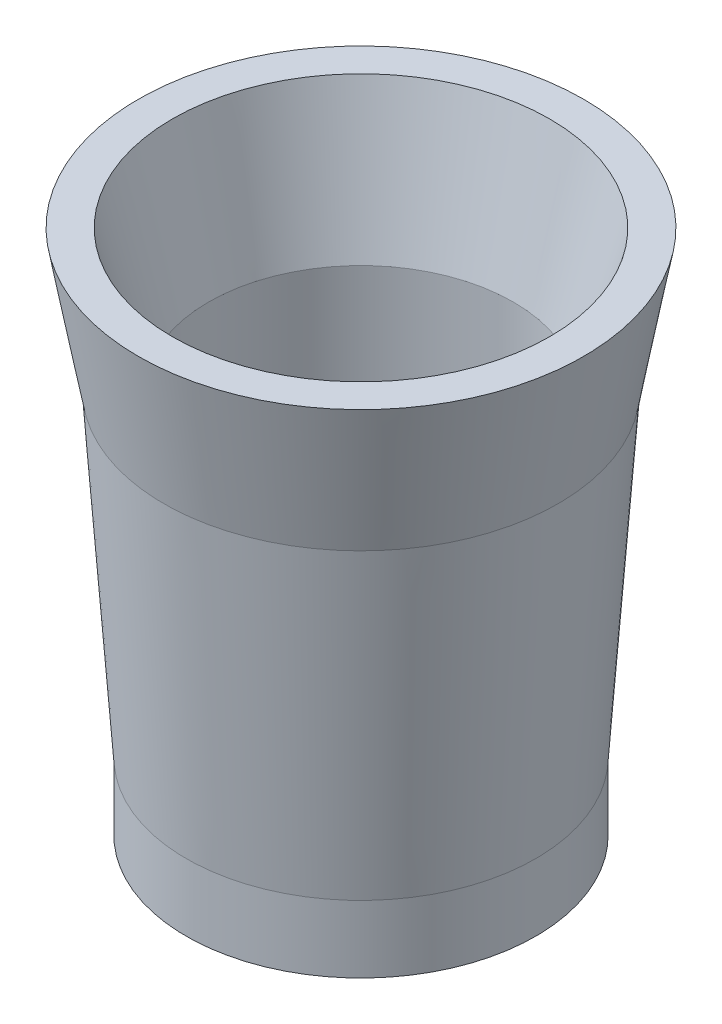
SolidWorks part; units mm, degrees
ref_plane "Front Plane" through (0, 0, 0) normal (0, 0, 1) x (1, 0, 0)
ref_plane "Top Plane" through (0, 0, 0) normal (0, 1, 0) x (1, 0, 0)
ref_plane "Right Plane" through (0, 0, 0) normal (1, 0, 0) x (0, 0, -1)
sketch "Sketch1" plane through (0, 0, 0) normal (0, 0, 1) x (1, 0, 0)
  line L0 (-19.939, 0) -> (19.939, 0) construction
  line L1 (19.939, 0) -> (61.1378, 58.838)
  line L2 (-19.939, 0) -> (-61.1378, 58.838)
  line L3 (-19.939, -109.3403) -> (-19.939, 58.838) construction
  line L4 (19.939, 58.838) -> (19.939, -109.3403) construction
  line L5 (19.939, 0) -> (43.18, -109.3403)
  line L6 (-19.939, 0) -> (-43.18, -109.3403)
  line L7 (0, 0) -> (0, -109.3403) construction
  line L8 (-43.18, -109.3403) -> (43.18, -109.3403) construction
  line L9 (-61.1378, 58.838) -> (61.1378, 58.838) construction
  line L10 (0, 0) -> (0, 58.838) construction
  line L11 (-69.85, 58.838) -> (69.85, 58.838) construction
  line L12 (-76.2, 58.838) -> (76.2, 58.838) construction
  line L13 (-61.1378, 58.838) -> (-69.85, 58.838)
  line L14 (-69.85, 58.838) -> (-69.85, 0)
  line L15 (-69.85, 0) -> (-76.2, 0)
  line L16 (-76.2, 0) -> (-76.2, -109.3403)
  line L17 (-76.2, -109.3403) -> (-43.18, -109.3403)
  line L18 (61.1378, 58.838) -> (69.85, 58.838)
  line L19 (69.85, 58.838) -> (69.85, 0)
  line L20 (69.85, 0) -> (76.2, 0)
  line L21 (76.2, 0) -> (76.2, -109.3403)
  line L22 (76.2, -109.3403) -> (43.18, -109.3403)
  line L23 (69.85, 39.788) -> (47.7988, 39.788)
  line L24 (-69.85, 39.788) -> (-47.7988, 39.788)
  line L25 (-76.2, 0) -> (76.2, 0) construction
  line L26 (-53.4699, 39.788) -> (-43.18, 0)
  line L27 (-43.18, 0) -> (-43.18, -76.2)
  line L28 (-43.18, -109.3403) -> (-43.18, -46.4417) construction
  line L29 (-43.18, -76.2) -> (-36.1358, -76.2)
  line L30 (-63.6778, 58.838) -> (63.6778, 58.838) construction
  line L31 (-69.85, 39.788) -> (-53.4699, 39.788) construction
  line L32 (-55.88, 0) -> (-49.53, -90.2903)
  line L33 (-63.1204, 39.788) -> (-63.1204, 35.0869) construction
  line L34 (-55.88, 0) -> (-63.1204, 39.788)
  line L35 (-43.18, -90.2903) -> (-62.0062, -90.2903) construction
  line L36 (-49.53, -90.2903) -> (-49.53, -109.3403)
  line L37 (43.18, -76.2) -> (36.1358, -76.2)
  line L38 (49.53, -90.2903) -> (49.53, -109.3403)
  line L39 (43.18, 0) -> (43.18, -76.2)
  line L40 (55.88, 0) -> (49.53, -90.2903)
  line L41 (55.88, 0) -> (63.1204, 39.788)
  line L42 (53.4699, 39.788) -> (43.18, 0)
  point P4 (0, 0)
  point P9 (-19.939, -25.2512)
  point P12 (19.939, 0)
  point P16 (0, 0)
  point P20 (0, -109.3403)
  point P22 (0, 58.838)
  point P25 (0, 58.838)
  point P37 (0, 0)
  point P39 (0, 0)
  point P46 (0, 58.838)
  dimension "D1" = 39.878
  dimension "D2" = 35
  dimension "D3" = 35
  dimension "D4" = 122.2756
  dimension "D5" = 12
  dimension "D6" = 86.36
  dimension "D7" = 139.7
  dimension "D8" = 152.4
  dimension "D9" = 19.05
  dimension "D10" = 19.05
  dimension "D11" = 152.4
  dimension "D12" = 20.5
  dimension "D13" = 12.7
  dimension "D14" = 6.35
  dimension "D15" = 127.3556
  dimension "D16" = 76.2
  dimension "D17" = 19.05
  dimension "D18" = 6.7296
ref_axis "Axis1" through (0, -120.4162, 0) along (0, 1, 0)
revolve "Revolve1" add sketch "Sketch1" angle 360 about axis through (0, -120.4162, 0) along (0, 1, 0)
